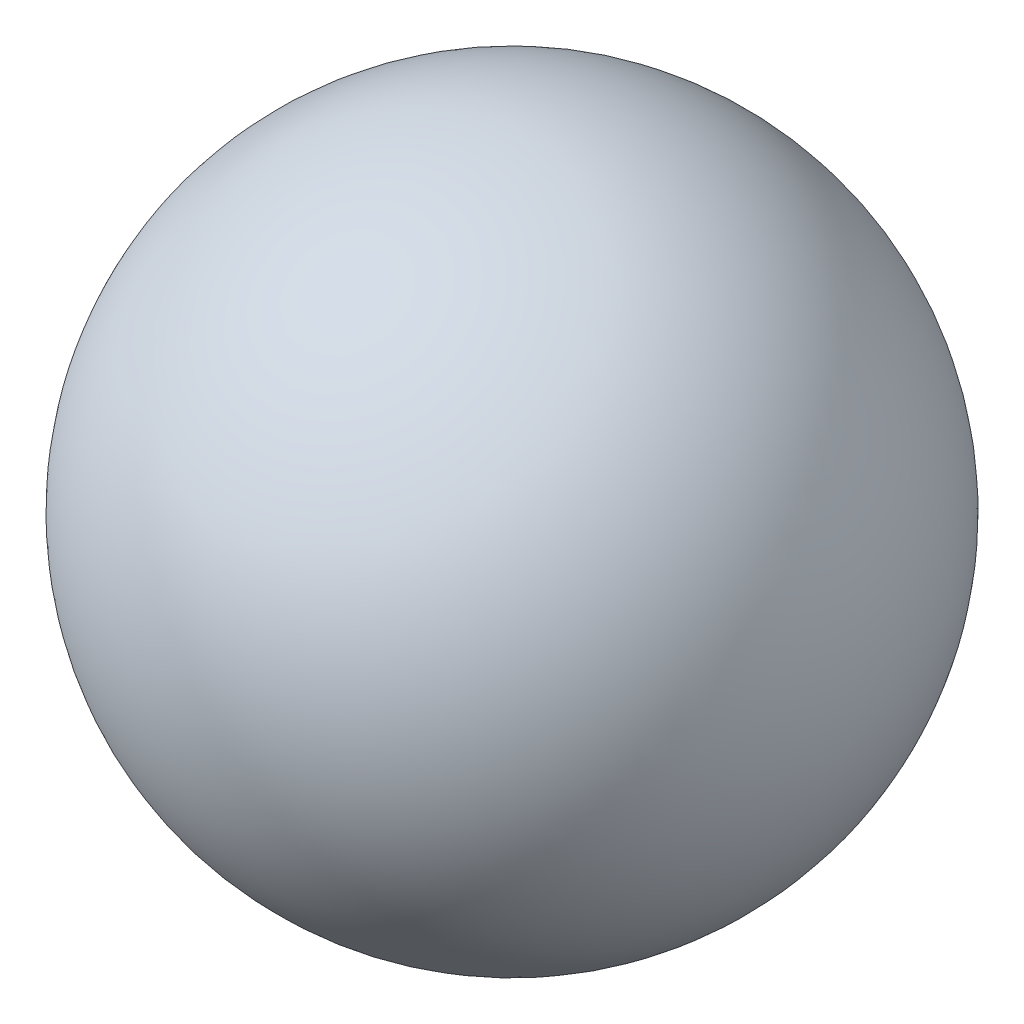
SolidWorks part; units mm, degrees
material "6061 Alloy"
ref_plane "Front Plane" through (0, 0, 0) normal (0, 0, 1) x (1, 0, 0)
ref_plane "Top Plane" through (0, 0, 0) normal (0, 1, 0) x (1, 0, 0)
ref_plane "Right Plane" through (0, 0, 0) normal (1, 0, 0) x (0, 0, -1)
sketch "Sketch1" plane through (0, 0, 0) normal (0, 1, 0) x (1, 0, 0)
  line L0 (0, 0) -> (341.122, 0) construction
  line L1 (-274.32, 0) -> (274.32, 0)
  arc A0 (274.32, 0) -> (-274.32, 0) centre (0, 0) ccw
  point P7 (341.122, 0)
  dimension "D1" = 548.64
  dimension "D2" = 341.122
revolve "Revolve6" add sketch "Sketch1" angle 360 about L0
shell "Shell1" thickness 3.175
